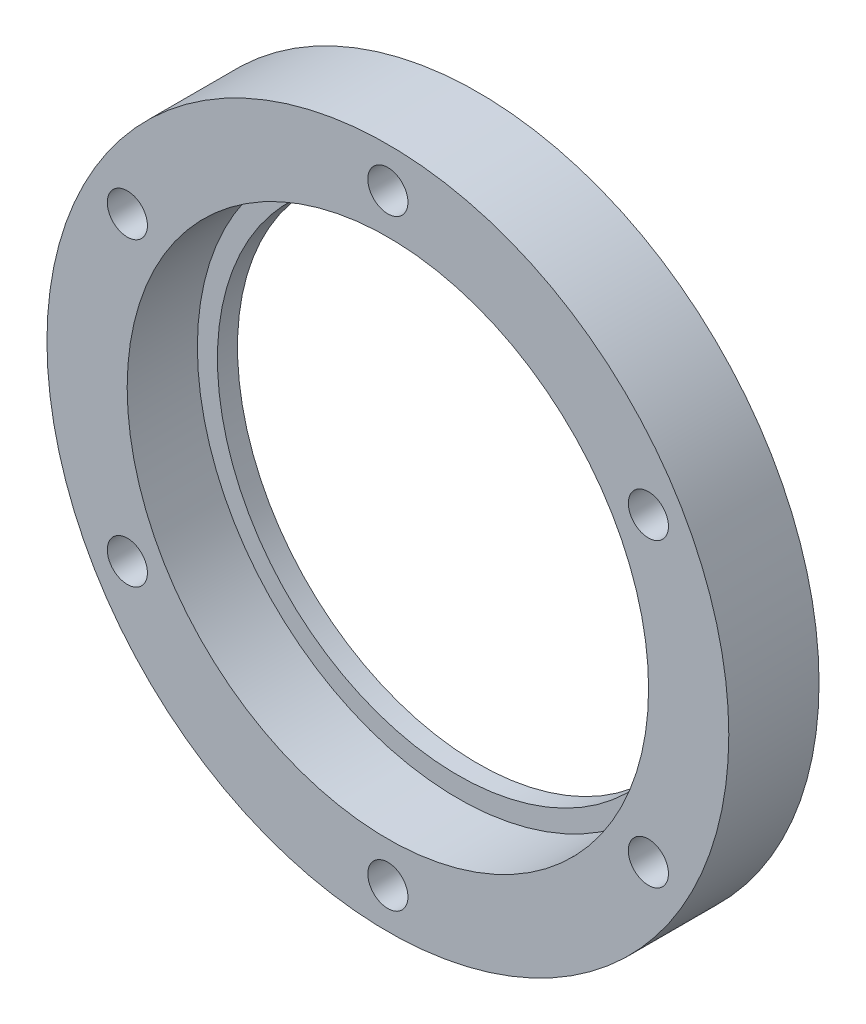
SolidWorks part; units mm, degrees
ref_plane "前视基准面" through (0, 0, 0) normal (0, 0, 1) x (1, 0, 0)
ref_plane "上视基准面" through (0, 0, 0) normal (0, 1, 0) x (1, 0, 0)
ref_plane "右视基准面" through (0, 0, 0) normal (1, 0, 0) x (0, 0, -1)
other "质心 (COM)"
sketch "草图1" plane through (0, 0, 0) normal (0, 0, 1) x (1, 0, 0)
  circle A0 centre (0, 0) radius 34
  dimension "D1" = 68
extrude "凸台-拉伸1" add sketch "草图1" along normal blind 9
sketch "草图2" plane through (0, 0, 9) normal (0, 0, 1) x (1, 0, 0)
  circle A0 centre (0, 0) radius 26
  dimension "D1" = 52
extrude "切除-拉伸1" cut sketch "草图2" against normal blind 7
sketch "草图3" plane through (0, 0, 2) normal (0, 0, 1) x (1, 0, 0)
  circle A0 centre (0, 0) radius 24
  dimension "D1" = 48
extrude "切除-拉伸2" cut sketch "草图3" against normal blind 8
sketch "草图4" plane through (0, 0, 9) normal (0, 0, 1) x (1, 0, 0)
  circle A0 centre (0, 30) radius 2
  circle A1 centre (25.9808, 15) radius 2
  circle A2 centre (25.9808, -15) radius 2
  circle A3 centre (0, -30) radius 2
  circle A4 centre (-25.9808, -15) radius 2
  circle A5 centre (-25.9808, 15) radius 2
  point P16 (0, 0)
  dimension "D1" = 30
  dimension "D2" = 4
  dimension "D3" = 6
extrude "切除-拉伸3" cut sketch "草图4" against normal through all
